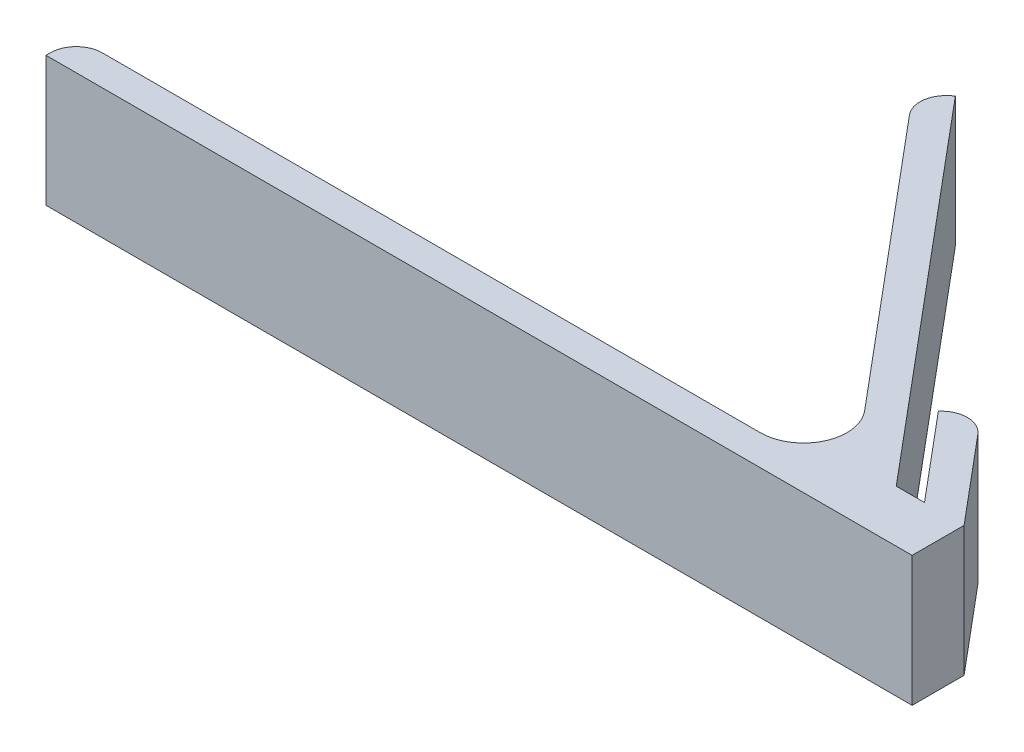
SolidWorks part; units mm, degrees
ref_plane "Front Plane" through (0, 0, 0) normal (0, 0, 1) x (1, 0, 0)
ref_plane "Top Plane" through (0, 0, 0) normal (0, 1, 0) x (1, 0, 0)
ref_plane "Right Plane" through (0, 0, 0) normal (1, 0, 0) x (0, 0, -1)
sketch "Sketch1" plane through (0, 0, 0) normal (0, 1, 0) x (1, 0, 0)
  line L0 (-46.1214, 46.1859) -> (-17.1959, 11.7139)
  line L2 (-21.0262, 3.5) -> (-100, 3.5)
  line L3 (-100, 3.5) -> (-100, 0)
  line L4 (-100, 0) -> (0, 0)
  line L5 (0, 0) -> (0, 6)
  line L6 (0, 6) -> (-10.244, 18.2083)
  line L7 (-10.244, 18.2083) -> (-12.9252, 15.9586)
  line L8 (-12.9252, 15.9586) -> (-4.5689, 6)
  line L9 (-4.5689, 6) -> (-7.8324, 6)
  line L10 (-7.8324, 6) -> (-43.4402, 48.4357)
  line L11 (-43.4402, 48.4357) -> (-46.1214, 46.1859)
  arc A0 (-21.0262, 3.5) -> (-17.1959, 11.7139) centre (-21.0262, 8.5) ccw
  dimension "D6" = 6
  dimension "D9" = 5
  dimension "D1" = 100
  dimension "D2" = 50
  dimension "D3" = 2.5
  dimension "D4" = 3.5
  dimension "D5" = 3.5
  dimension "D7" = 13
  dimension "D8" = 45
extrude "Boss-Extrude1" add sketch "Sketch1" along normal blind 15
fillet "Fillet1" radius 3 3 edges at (-100, 7.5, -3.5) (-46.1214, 7.5, -46.1859) (-10.244, 7.5, -18.2083)
